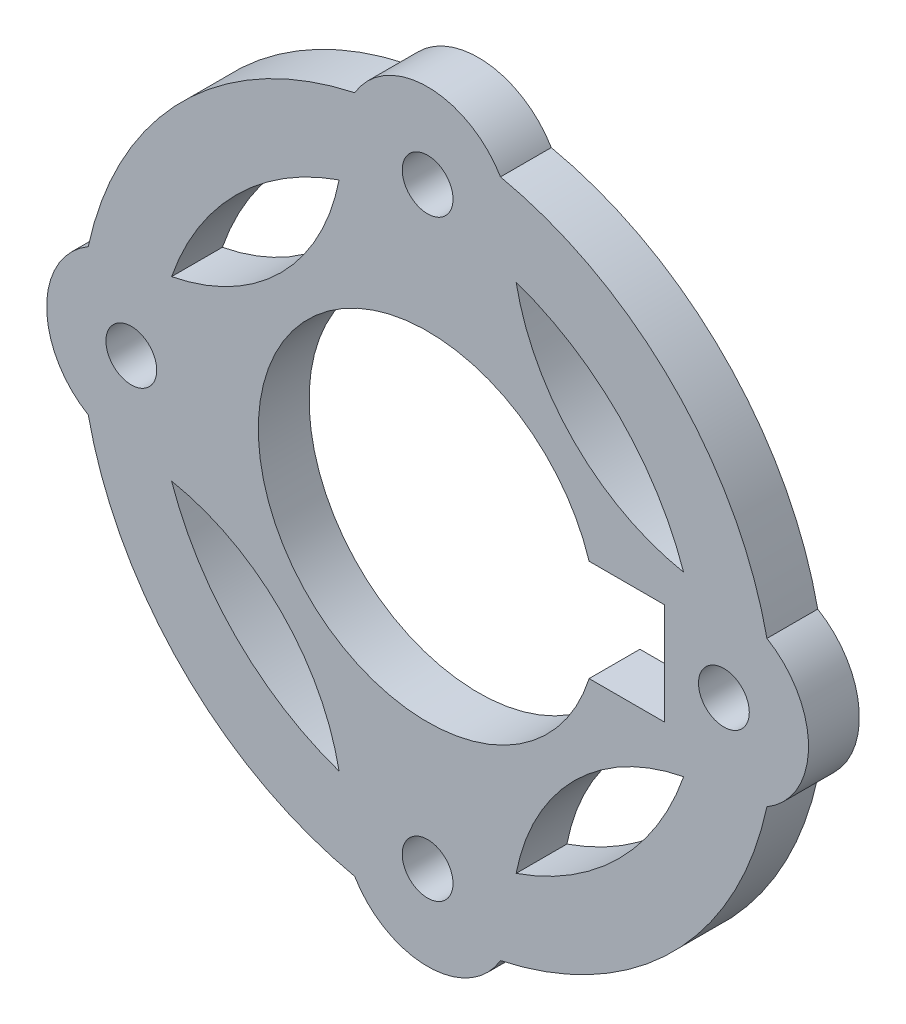
SolidWorks part; units mm, degrees
material "Acrílico (Impacto medio-alto)"
ref_plane "Alzado" through (0, 0, 0) normal (0, 0, 1) x (1, 0, 0)
ref_plane "Planta" through (0, 0, 0) normal (0, 1, 0) x (1, 0, 0)
ref_plane "Vista lateral" through (0, 0, 0) normal (1, 0, 0) x (0, 0, -1)
sketch "Croquis2" plane through (0, 0, 0) normal (0, 0, 1) x (1, 0, 0)
  circle A1 centre (0, 17.5) radius 1.5
  circle A2 centre (0, 17.5) radius 5
  circle A3 centre (17.5, 0) radius 1.5
  circle A4 centre (17.5, 0) radius 5
  circle A5 centre (0, -17.5) radius 1.5
  circle A6 centre (0, -17.5) radius 5
  circle A7 centre (-17.5, 0) radius 1.5
  circle A8 centre (-17.5, 0) radius 5
  circle A9 centre (0, 0) radius 10
  circle A10 centre (0, 17.5) radius 3
  circle A11 centre (17.5, 0) radius 3
  circle A12 centre (0, -17.5) radius 3
  circle A13 centre (-17.5, 0) radius 3
  arc A14 (-5, 17.5) -> (-17.5, 5) centre (-17.5, 17.5) cw
  arc A15 (5, 17.5) -> (17.5, 5) centre (17.5, 17.5) ccw
  arc A16 (17.5, -5) -> (5, -17.5) centre (17.5, -17.5) ccw
  arc A17 (-5, -17.5) -> (-17.5, -5) centre (-17.5, -17.5) ccw
  circle A20 centre (0, 0) radius 16
  circle A21 centre (0, 0) radius 20.5
  dimension "D2" = 10
  dimension "D3" = 3
  dimension "D4" = 10
  dimension "D5" = 3
  dimension "D6" = 10
  dimension "D7" = 3
  dimension "D8" = 10
  dimension "D9" = 3
  dimension "D10" = 20
  dimension "D11" = 6
  dimension "D12" = 6
  dimension "D13" = 6
  dimension "D14" = 6
extrude "Saliente-Extruir2" add sketch "Croquis2" along normal blind 3
sketch "Croquis4" plane through (0, 0, 0) normal (0, 0, -1) x (-1, 0, 0)
  line L1 (-14, 3) -> (-6, 3)
  line L2 (-14, 3) -> (-14, -3)
  line L3 (-14, -3) -> (-6, -3)
  line L4 (-6, 3) -> (-6, -3)
  line L5 (-14, 3) -> (-6, -3) construction
  line L6 (-14, -3) -> (-6, 3) construction
  circle A0 centre (0, 0) radius 10 construction
  point P0 (-10, 0)
  dimension "D1" = 8
  dimension "D2" = 6
extrude "Cortar-Extruir1" cut sketch "Croquis4" against normal through all
